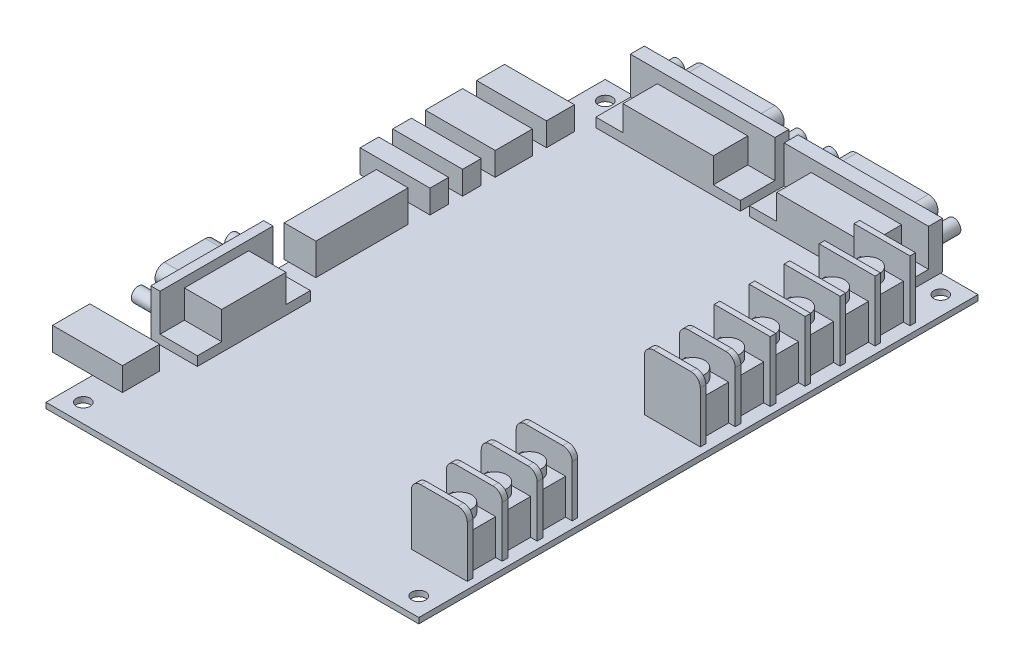
SolidWorks part; units mm, degrees
material "ASTM A36 Steel"
ref_plane "Front Plane" through (0, 0, 0) normal (0, 0, 1) x (1, 0, 0)
ref_plane "Top Plane" through (0, 0, 0) normal (0, 1, 0) x (1, 0, 0)
ref_plane "Right Plane" through (0, 0, 0) normal (1, 0, 0) x (0, 0, -1)
sketch "Sketch1" plane through (0, 0, 0) normal (0, 1, 0) x (1, 0, 0)
  line L1 (-50.8, 76.2) -> (50.8, 76.2)
  line L2 (-50.8, 76.2) -> (-50.8, -76.2)
  line L3 (-50.8, -76.2) -> (50.8, -76.2)
  line L4 (50.8, 76.2) -> (50.8, -76.2)
  circle A0 centre (45.72, 71.12) radius 1.905
  circle A1 centre (-45.72, 71.12) radius 1.905
  circle A2 centre (-45.72, -71.12) radius 1.905
  circle A3 centre (45.72, -71.12) radius 1.905
  point P4 (50.8, 0)
  point P5 (0, 76.2)
  dimension "D4" = 45.72
  dimension "D7" = 3.81
  dimension "D1" = 101.6
  dimension "D2" = 152.4
  dimension "D3" = 45.72
  dimension "D5" = 71.12
  dimension "D6" = 71.12
extrude "Boss-Extrude1" add sketch "Sketch1" along normal blind 1.524
sketch "Sketch2" plane through (0, 1.524, 0) normal (0, 1, 0) x (1, 0, 0)
  line L1 (35.433, -31.75) -> (47.117, -31.75)
  line L2 (35.433, -31.75) -> (35.433, -60.325)
  line L3 (35.433, -60.325) -> (47.117, -60.325)
  line L4 (47.117, -31.75) -> (47.117, -60.325)
  line L5 (35.433, 60.325) -> (47.117, 60.325)
  line L6 (35.433, 60.325) -> (35.433, 3.175)
  line L7 (35.433, 3.175) -> (47.117, 3.175)
  line L8 (47.117, 60.325) -> (47.117, 3.175)
  point P8 (41.275, 60.325)
  point P10 (41.275, -31.75)
  dimension "D1" = 3.175
  dimension "D2" = 31.75
  dimension "D3" = 57.15
  dimension "D4" = 28.575
  dimension "D5" = 41.275
  dimension "D6" = 11.684
extrude "Boss-Extrude2" add sketch "Sketch2" along normal blind 9.652
sketch "Sketch3" plane through (0, 1.524, 0) normal (0, 1, 0) x (1, 0, 0)
  line L0 (35.433, -60.325) -> (47.117, -60.325) construction
  line L1 (33.655, -59.563) -> (48.895, -59.563)
  line L2 (33.655, -59.563) -> (33.655, -61.087)
  line L3 (33.655, -61.087) -> (48.895, -61.087)
  line L4 (48.895, -59.563) -> (48.895, -61.087)
  line L5 (35.433, 3.175) -> (47.117, 3.175) construction
  line L6 (33.655, 3.937) -> (48.895, 3.937)
  line L7 (33.655, 3.937) -> (33.655, 2.413)
  line L8 (33.655, 2.413) -> (48.895, 2.413)
  line L9 (48.895, 3.937) -> (48.895, 2.413)
  point P4 (48.895, -60.325)
  point P5 (41.275, -59.563)
  point P13 (48.895, 3.175)
  point P14 (41.275, 3.937)
  dimension "D1" = 1.524
  dimension "D2" = 15.24
extrude "Boss-Extrude3" add sketch "Sketch3" along normal blind 16.51
fillet "Fillet1" radius 2.54 4 edges at (33.655, 18.034, 60.325) (48.895, 18.034, 60.325) (33.655, 18.034, -3.175) (48.895, 18.034, -3.175)
sketch "Sketch4" plane through (0, 11.176, 0) normal (0, 1, 0) x (1, 0, 0)
  line L0 (35.433, -60.325) -> (47.117, -60.325) construction
  circle A0 centre (41.275, -55.5498) radius 3.302
  dimension "D1" = 6.604
  dimension "D2" = 4.7752
extrude "Boss-Extrude4" add sketch "Sketch4" along normal blind 2.54
sketch "Sketch5" plane through (0, 1.524, 0) normal (0, 1, 0) x (1, 0, 0)
  line L0 (48.895, -59.563) -> (48.895, -61.087) construction
  line L1 (33.655, -50.038) -> (48.895, -50.038)
  line L2 (33.655, -50.038) -> (33.655, -51.562)
  line L3 (33.655, -51.562) -> (48.895, -51.562)
  line L4 (48.895, -50.038) -> (48.895, -51.562)
  line L5 (33.655, -61.087) -> (48.895, -61.087) construction
  dimension "D1" = 9.525
extrude "Boss-Extrude5" add sketch "Sketch5" along normal blind 16.51
fillet "Fillet2" radius 2.54 2 edges at (33.655, 18.034, 50.8) (48.895, 18.034, 50.8)
pattern_linear "LPattern1" count 3 spacing 9.525 along (0, 0, -1) of "Boss-Extrude5", "Fillet2", "Boss-Extrude4"
sketch "Sketch6" plane through (0, 1.524, 0) normal (0, 1, 0) x (1, 0, 0)
  line L0 (48.895, 3.937) -> (48.895, 2.413) construction
  line L1 (33.655, 13.462) -> (48.895, 13.462)
  line L2 (33.655, 13.462) -> (33.655, 11.938)
  line L3 (33.655, 11.938) -> (48.895, 11.938)
  line L4 (48.895, 13.462) -> (48.895, 11.938)
  line L5 (33.655, 2.413) -> (48.895, 2.413) construction
  dimension "D1" = 9.525
extrude "Boss-Extrude6" add sketch "Sketch6" along normal blind 16.51
sketch "Sketch7" plane through (0, 11.176, 0) normal (0, 1, 0) x (1, 0, 0)
  line L0 (35.433, 3.175) -> (47.117, 3.175) construction
  circle A0 centre (41.275, 7.9502) radius 3.302
  dimension "D2" = 6.604
  dimension "D1" = 4.7752
extrude "Boss-Extrude7" add sketch "Sketch7" along normal blind 2.54
fillet "Fillet3" radius 2.54 2 edges at (33.655, 18.034, -12.7) (48.895, 18.034, -12.7)
pattern_linear "LPattern2" count 6 spacing 9.525 along (0, 0, -1) of "Boss-Extrude6", "Boss-Extrude7"
sketch "Sketch8" plane through (0, 1.524, 0) normal (0, 1, 0) x (1, 0, 0)
  line L0 (-50.8, 76.2) -> (50.8, 76.2) construction
  line L1 (1.27, 76.708) -> (40.64, 76.708)
  line L2 (1.27, 76.708) -> (1.27, 63.5)
  line L3 (1.27, 63.5) -> (40.64, 63.5)
  line L4 (40.64, 76.708) -> (40.64, 63.5)
  point P4 (20.955, 76.708)
  dimension "D1" = 0.508
  dimension "D2" = 39.37
  dimension "D3" = 20.955
  dimension "D4" = 13.208
extrude "Boss-Extrude8" add sketch "Sketch8" along normal blind 2.54
sketch "Sketch9" plane through (0, 1.524, 0) normal (0, 1, 0) x (1, 0, 0)
  line L0 (1.27, 63.5) -> (40.64, 63.5) construction
  line L1 (8.636, 76.708) -> (33.274, 76.708)
  line L2 (8.636, 76.708) -> (8.636, 63.5)
  line L3 (8.636, 63.5) -> (33.274, 63.5)
  line L4 (33.274, 76.708) -> (33.274, 63.5)
  dimension "D1" = 24.638
extrude "Boss-Extrude9" add sketch "Sketch9" along normal blind 9.398
sketch "Sketch10" plane through (0, 1.524, 0) normal (0, 1, 0) x (1, 0, 0)
  line L1 (1.27, 76.708) -> (40.64, 76.708)
  line L2 (1.27, 76.708) -> (1.27, 72.898)
  line L3 (1.27, 72.898) -> (40.64, 72.898)
  line L4 (40.64, 76.708) -> (40.64, 72.898)
  dimension "D1" = 3.81
extrude "Boss-Extrude10" add sketch "Sketch10" along normal blind 12.7
sketch "Sketch11" plane through (0, 0, -76.708) normal (0, 0, -1) x (-1, 0, 0)
  line L0 (-20.955, 11.8618) -> (-20.955, 3.8862) construction
  line L1 (-11.1506, 11.8618) -> (-30.7594, 11.8618)
  line L2 (-8.6492, 8.8807) -> (-9.1598, 5.9851)
  line L3 (-11.6612, 3.8862) -> (-30.2488, 3.8862)
  line L4 (-33.2608, 8.8807) -> (-32.7502, 5.9851)
  circle A0 centre (-4.2926, 7.874) radius 1.905
  circle A1 centre (-37.6174, 7.874) radius 1.905
  arc A2 (-11.1506, 11.8618) -> (-8.6492, 8.8807) centre (-11.1506, 9.3218) cw
  arc A3 (-9.1598, 5.9851) -> (-11.6612, 3.8862) centre (-11.6612, 6.4262) cw
  arc A4 (-32.7502, 5.9851) -> (-30.2488, 3.8862) centre (-30.2488, 6.4262) ccw
  arc A5 (-30.7594, 11.8618) -> (-33.2608, 8.8807) centre (-30.7594, 9.3218) ccw
  point P14 (-20.955, 7.874)
  dimension "D1" = 2.54
  dimension "D2" = 3.81
  dimension "D4" = 24.6888
  dimension "D3" = 33.3248
  dimension "D5" = 6.35
  dimension "D6" = 7.9756
  dimension "D7" = 80
extrude "Boss-Extrude11" add sketch "Sketch11" along normal blind 6.096
mirror "Mirror1" about plane through (0, 0, 0) normal (1, 0, 0) of "Boss-Extrude11", "Boss-Extrude10", "Boss-Extrude9", "Boss-Extrude8"
sketch "Sketch12" plane through (0, 1.524, 0) normal (0, 1, 0) x (1, 0, 0)
  line L0 (-50.8, 76.2) -> (-50.8, -76.2) construction
  line L1 (-51.308, -16.3576) -> (-38.608, -16.3576)
  line L2 (-51.308, -16.3576) -> (-51.308, -47.1424)
  line L3 (-51.308, -47.1424) -> (-38.608, -47.1424)
  line L4 (-38.608, -16.3576) -> (-38.608, -47.1424)
  point P4 (-51.308, -31.75)
  dimension "D1" = 0.508
  dimension "D2" = 12.7
  dimension "D3" = 30.7848
  dimension "D4" = 31.75
extrude "Boss-Extrude12" add sketch "Sketch12" along normal blind 2.54
sketch "Sketch13" plane through (0, 1.524, 0) normal (0, 1, 0) x (1, 0, 0)
  line L0 (-38.608, -16.3576) -> (-38.608, -47.1424) construction
  line L1 (-51.308, -22.987) -> (-38.608, -22.987)
  line L2 (-51.308, -22.987) -> (-51.308, -40.513)
  line L3 (-51.308, -40.513) -> (-38.608, -40.513)
  line L4 (-38.608, -22.987) -> (-38.608, -40.513)
  dimension "D1" = 17.526
extrude "Boss-Extrude13" add sketch "Sketch13" along normal blind 10.16
sketch "Sketch14" plane through (0, 1.524, 0) normal (0, 1, 0) x (1, 0, 0)
  line L1 (-51.308, -16.3576) -> (-48.768, -16.3576)
  line L2 (-51.308, -16.3576) -> (-51.308, -47.1424)
  line L3 (-51.308, -47.1424) -> (-48.768, -47.1424)
  line L4 (-48.768, -16.3576) -> (-48.768, -47.1424)
  dimension "D1" = 2.54
extrude "Boss-Extrude14" add sketch "Sketch14" along normal blind 12.7
sketch "Sketch15" plane through (-51.308, 0, 0) normal (-1, 0, 0) x (0, 0, 1)
  line L0 (26.6636, 3.9116) -> (36.8364, 3.9116)
  line L1 (39.3378, 6.0105) -> (39.8394, 8.8553)
  line L2 (37.338, 11.8364) -> (26.162, 11.8364)
  line L3 (31.75, 11.8364) -> (31.75, 3.9116) construction
  line L4 (16.3576, 1.524) -> (47.1424, 1.524) construction
  line L5 (24.1622, 6.0105) -> (23.6606, 8.8553)
  circle A0 centre (44.45, 7.874) radius 1.905
  arc A1 (39.8394, 8.8553) -> (37.338, 11.8364) centre (37.338, 9.2964) ccw
  arc A2 (36.8364, 3.9116) -> (39.3378, 6.0105) centre (36.8364, 6.4516) ccw
  circle A3 centre (19.05, 7.874) radius 1.905
  arc A4 (26.6636, 3.9116) -> (24.1622, 6.0105) centre (26.6636, 6.4516) cw
  arc A5 (23.6606, 8.8553) -> (26.162, 11.8364) centre (26.162, 9.2964) cw
  point P8 (31.75, 7.874)
  point P9 (31.75, 1.524)
  dimension "D1" = 3.81
  dimension "D2" = 25.4
  dimension "D5" = 2.54
  dimension "D6" = 16.256
  dimension "D3" = 6.35
  dimension "D4" = 80
  dimension "D7" = 7.9248
extrude "Boss-Extrude15" add sketch "Sketch15" along normal blind 6.096
sketch "Sketch16" plane through (0, 1.524, 0) normal (0, 1, 0) x (1, 0, 0)
  line L0 (-50.8, 76.2) -> (-50.8, -76.2) construction
  line L1 (-61.722, 59.69) -> (-42.672, 59.69)
  line L2 (-61.722, 59.69) -> (-61.722, 52.07)
  line L3 (-61.722, 52.07) -> (-42.672, 52.07)
  line L4 (-42.672, 59.69) -> (-42.672, 52.07)
  line L5 (-61.722, 48.26) -> (-42.672, 48.26)
  line L6 (-61.722, 48.26) -> (-61.722, 38.1)
  line L7 (-61.722, 38.1) -> (-42.672, 38.1)
  line L8 (-42.672, 48.26) -> (-42.672, 38.1)
  line L9 (-61.722, 34.29) -> (-42.672, 34.29)
  line L10 (-61.722, 34.29) -> (-61.722, 29.21)
  line L11 (-61.722, 29.21) -> (-42.672, 29.21)
  line L12 (-42.672, 34.29) -> (-42.672, 29.21)
  line L13 (-61.722, 25.4) -> (-42.672, 25.4)
  line L14 (-61.722, 25.4) -> (-61.722, 20.32)
  line L15 (-61.722, 20.32) -> (-42.672, 20.32)
  line L16 (-42.672, 25.4) -> (-42.672, 20.32)
  line L17 (-61.722, -53.34) -> (-42.672, -53.34)
  line L18 (-61.722, -53.34) -> (-61.722, -63.5)
  line L19 (-61.722, -63.5) -> (-42.672, -63.5)
  line L20 (-42.672, -53.34) -> (-42.672, -63.5)
  line L21 (-50.8, 76.2) -> (50.8, 76.2) construction
  line L22 (-50.8, -76.2) -> (50.8, -76.2) construction
  dimension "D1" = 8.128
  dimension "D2" = 19.05
  dimension "D3" = 16.51
  dimension "D4" = 7.62
  dimension "D5" = 3.81
  dimension "D6" = 10.16
  dimension "D7" = 3.81
  dimension "D8" = 5.08
  dimension "D9" = 3.81
  dimension "D10" = 5.08
  dimension "D11" = 12.7
  dimension "D12" = 10.16
extrude "Boss-Extrude16" add sketch "Sketch16" along normal blind 6.35
sketch "Sketch17" plane through (0, 1.524, 0) normal (0, 1, 0) x (1, 0, 0)
  line L1 (-52.07, 15.113) -> (-43.434, 15.113)
  line L2 (-52.07, 15.113) -> (-52.07, -10.033)
  line L3 (-52.07, -10.033) -> (-43.434, -10.033)
  line L4 (-43.434, 15.113) -> (-43.434, -10.033)
  line L6 (-50.8, 76.2) -> (-50.8, -76.2) construction
  point P6 (-52.07, 2.54)
  dimension "D1" = 1.27
  dimension "D2" = 8.636
  dimension "D3" = 25.146
  dimension "D4" = 2.54
extrude "Boss-Extrude17" add sketch "Sketch17" along normal blind 8.636
